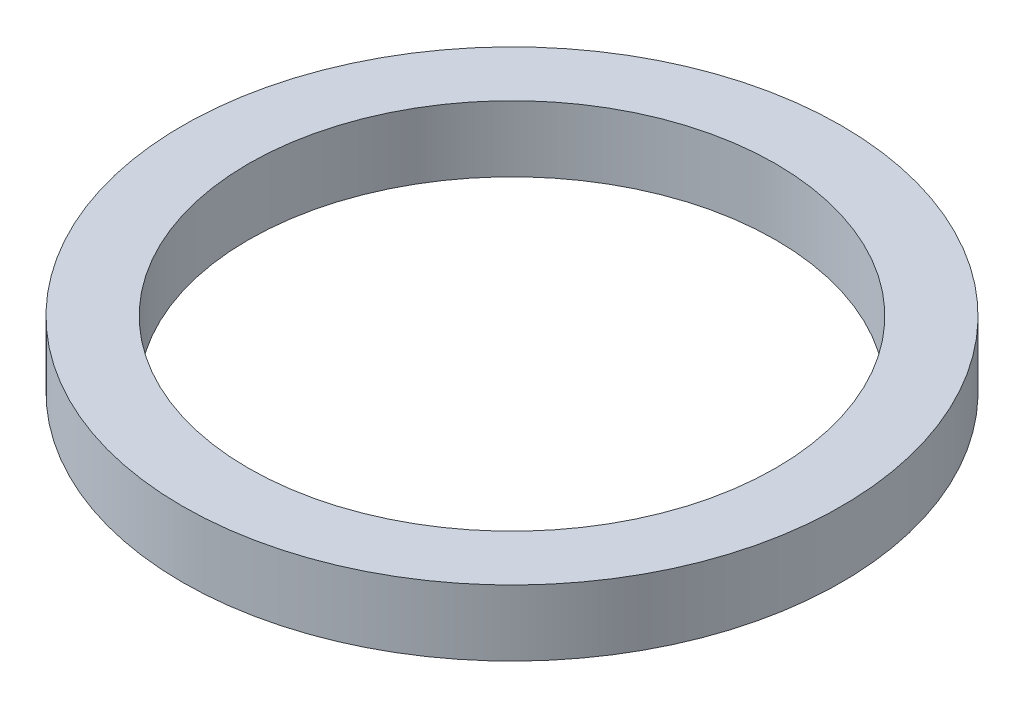
SolidWorks part; units mm, degrees
ref_plane "Front Plane" through (0, 0, 0) normal (0, 0, 1) x (1, 0, 0)
ref_plane "Top Plane" through (0, 0, 0) normal (0, 1, 0) x (1, 0, 0)
ref_plane "Right Plane" through (0, 0, 0) normal (1, 0, 0) x (0, 0, -1)
sketch "Sketch1" plane through (0, 0, 0) normal (0, 1, 0) x (1, 0, 0)
  circle A0 centre (0, 0) radius 50
  circle A1 centre (0, 0) radius 40
  dimension "D1" = 100
  dimension "D2" = 80
extrude "Boss-Extrude1" add sketch "Sketch1" along normal blind 10
